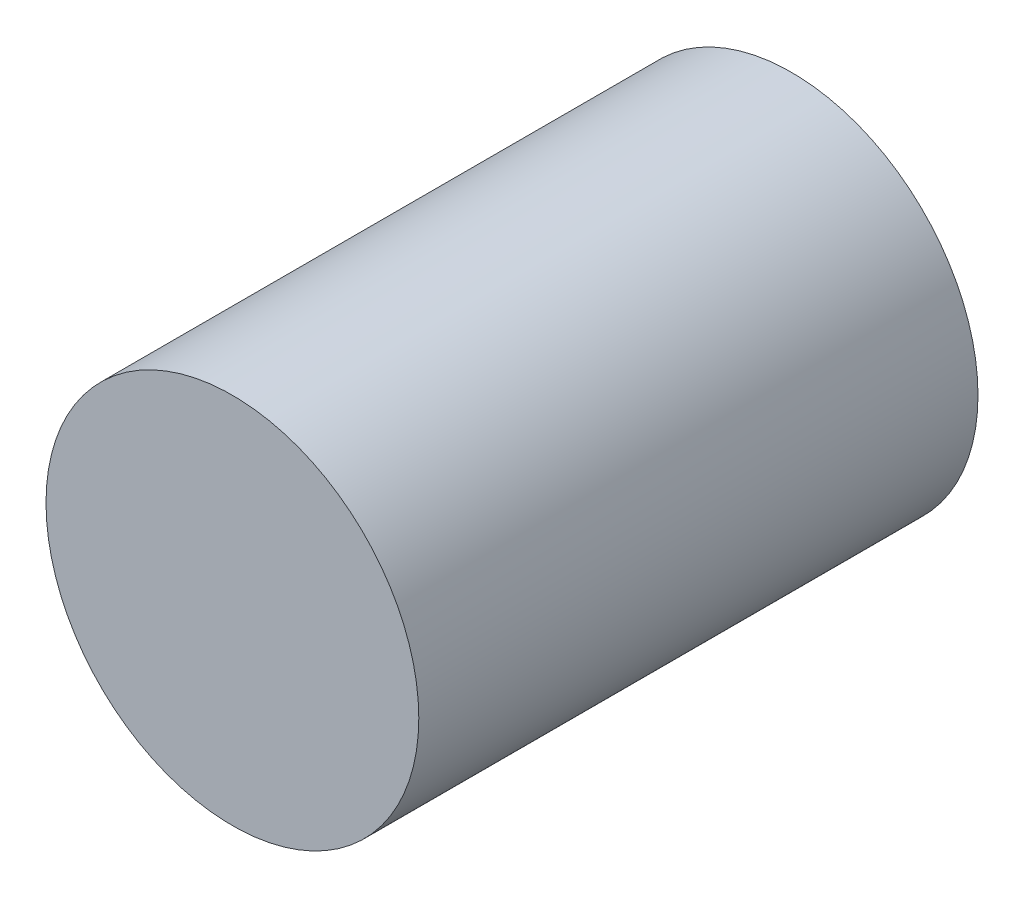
SolidWorks part; units mm, degrees
ref_plane "Plan de face" through (0, 0, 0) normal (0, 0, 1) x (1, 0, 0)
ref_plane "Plan de dessus" through (0, 0, 0) normal (0, 1, 0) x (1, 0, 0)
ref_plane "Plan de droite" through (0, 0, 0) normal (1, 0, 0) x (0, 0, -1)
sketch "Esquisse1" plane through (0, 0, 0) normal (0, 0, 1) x (1, 0, 0)
  circle A0 centre (0, 0) radius 10
  dimension "D1" = 20
extrude "Boss.-Extru.1" add sketch "Esquisse1" along normal blind 30
sketch "Esquisse2" plane through (0, 0, 0) normal (0, 0, -1) x (-1, 0, 0)
  circle A0 centre (0, 0) radius 2.5
  dimension "D1" = 5
extrude "Enlèv. mat.-Extru.1" cut sketch "Esquisse2" against normal blind 10
